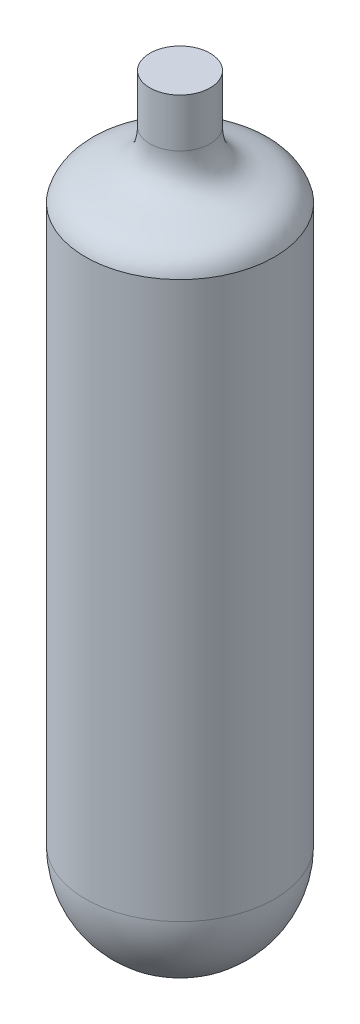
SolidWorks part; units mm, degrees
ref_plane "Front Plane" through (0, 0, 0) normal (0, 0, 1) x (1, 0, 0)
ref_plane "Top Plane" through (0, 0, 0) normal (0, 1, 0) x (1, 0, 0)
ref_plane "Right Plane" through (0, 0, 0) normal (1, 0, 0) x (0, 0, -1)
sketch "Sketch1" plane through (0, 0, 0) normal (0, 0, 1) x (1, 0, 0)
  line L0 (0, 0) -> (0, 45.6127) construction
  line L1 (-11, 39) -> (11, 39)
  line L2 (-11, 39) -> (-11, -39)
  line L3 (-11, -39) -> (11, -39)
  line L4 (11, 39) -> (11, -39)
  line L5 (-11, 39) -> (11, -39) construction
  line L6 (-11, -39) -> (11, 39) construction
  line L7 (3.5, 28) -> (0, 28)
  line L8 (3.5, 28) -> (3.5, 50)
  line L9 (3.5, 50) -> (0, 50)
  line L10 (0, 28) -> (0, 50)
  line L11 (3.5, 28) -> (0, 50) construction
  line L12 (3.5, 50) -> (0, 28) construction
  line L13 (0, -39) -> (0, -28) construction
  line L14 (0, 28) -> (0, -39)
  arc A0 (-11, -28) -> (11, -28) centre (0, -28) ccw
  spline S0 degree 3 poles (3.5, 44.3644) (3.4019, 38.217) (9.7943, 41.0727) (11, 36.7062) knots 0 0 0 0 1 1 1 1
  point P0 (0, 0)
  point P6 (1.75, 39)
  dimension "D1" = 11
  dimension "D2" = 89
  dimension "D3" = 22
  dimension "D4" = 3.5
  dimension "D5" = 11
revolve "Revolve1" add sketch "Sketch1" angle 360 about L14
